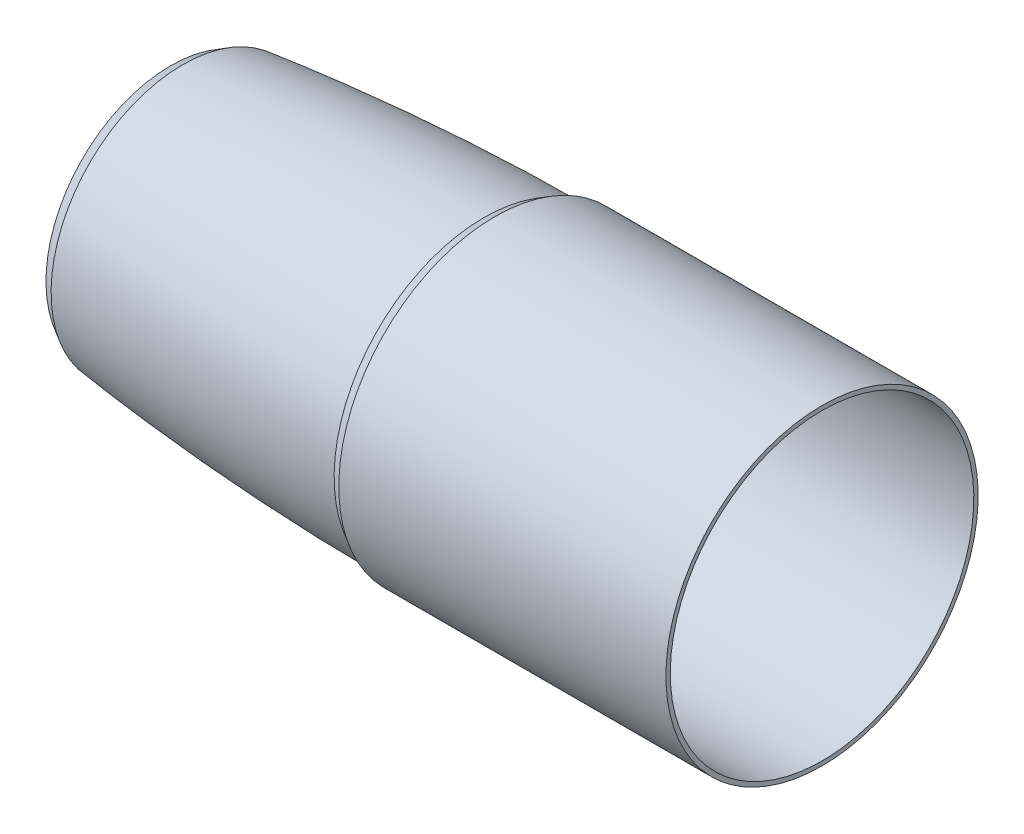
SolidWorks part; units mm, degrees
ref_plane "Front Plane" through (0, 0, 0) normal (0, 0, 1) x (1, 0, 0)
ref_plane "Top Plane" through (0, 0, 0) normal (0, 1, 0) x (1, 0, 0)
ref_plane "Right Plane" through (0, 0, 0) normal (1, 0, 0) x (0, 0, -1)
sketch "Sketch1" plane through (0, 0, 0) normal (0, 0, 1) x (1, 0, 0)
  line L0 (0, 0) -> (-229, 0) construction
  line L1 (0, 36.6) -> (0, -642.3338) construction
  line L3 (-229, 0) -> (-219.9054, 0)
  line L4 (83, 38.5) -> (3.2909, 38.5)
  line L7 (0, 39.6) -> (83, 39.6)
  line L8 (83, 38.5) -> (83, 39.6)
  line L9 (0, 36.6) -> (3.2909, 38.5)
  line L10 (0, 36.6) -> (119.7357, 36.6) construction
  line L11 (3.2909, 38.5) -> (119.7357, 38.5) construction
  line L12 (119.7357, 36.6) -> (119.7357, 38.5) construction
  line L13 (-79.2, 81.783) -> (-79.2, 33.3743) construction
  line L15 (0, 39.6) -> (-2.7811, 37.9943)
  line L16 (-79.2, 33.3743) -> (-82.2806, 31.5957)
  line L17 (-79.2, 31.9647) -> (-79.2, -62.4632) construction
  circle A0 centre (0, -642.3338) radius 681.9338 construction
  arc A1 (-229, 0) -> (0, 39.6) centre (0, -642.3338) cw
  arc A2 (-219.9054, 0) -> (0, 36.6) centre (0, -642.3338) cw
  arc A3 (-227.9926, -2.8258) -> (0, 36.6) centre (0, -642.3338) cw construction
  arc A4 (-79.2, 33.3743) -> (-2.7811, 37.9943) centre (0, -642.3338) cw
  arc A5 (-220.3589, 1.3245) -> (0, 38) centre (0, -642.3338) cw construction
  point P0 (0, 39.6)
  dimension "D1" = 39.6
  dimension "D2" = 229
  dimension "D3" = 681.9338
  dimension "D5" = 83
  dimension "D6" = 1.1
  dimension "D7" = 30
  dimension "D8" = 79.7091
  dimension "D9" = 1.9
  dimension "D10" = 38.5
  dimension "D11" = 1.4
  dimension "D12" = 79.2
  dimension "D13" = 30
  dimension "D14" = 30
  dimension "D4" = 3
revolve "Revolve1" add sketch "Sketch1" angle 360 about L0
